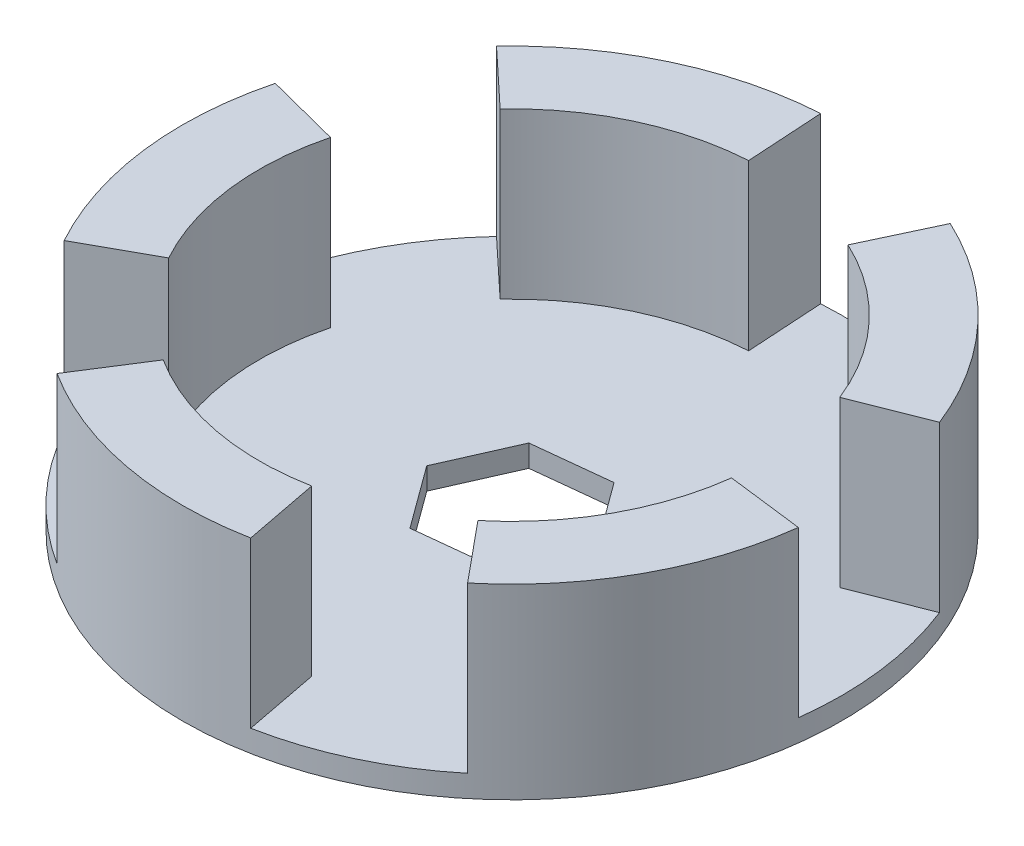
SolidWorks part; units mm, degrees
ref_plane "Front Plane" through (0, 0, 0) normal (0, 0, 1) x (1, 0, 0)
ref_plane "Top Plane" through (0, 0, 0) normal (0, 1, 0) x (1, 0, 0)
ref_plane "Right Plane" through (0, 0, 0) normal (1, 0, 0) x (0, 0, -1)
sketch "Sketch3" plane through (0, 0, 0) normal (0, 1, 0) x (1, 0, 0)
  circle A0 centre (0, 0) radius 30
  dimension "D2" = 60
extrude "Boss-Extrude3" add sketch "Sketch3" along normal blind 2
sketch "Sketch4" plane through (0, 2, 0) normal (0, 1, 0) x (1, 0, 0)
  line L0 (0, 0) -> (-16.7954, 15.7135) construction
  line L1 (0, 0) -> (9.7544, 20.8291) construction
  line L2 (0, 0) -> (21.3954, 8.4401) construction
  line L3 (0, 0) -> (22.8239, -2.8404) construction
  line L4 (0, 0) -> (14.6386, -17.7401) construction
  line L5 (0, 0) -> (4.3516, -22.5846) construction
  line L6 (0, 0) -> (-12.3483, -19.4041) construction
  line L7 (0, 0) -> (-20.1345, -11.1176) construction
  line L8 (0, 0) -> (-22.2702, 5.7477) construction
  line L9 (0, 0) -> (-1.4155, 22.9564) construction
  line L10 (-16.7954, 15.7135) -> (-1.4155, 22.9564) construction
  line L11 (-1.4155, 22.9564) -> (9.7544, 20.8291) construction
  line L12 (9.7544, 20.8291) -> (21.3954, 8.4401) construction
  line L13 (21.3954, 8.4401) -> (22.8239, -2.8404) construction
  line L14 (22.8239, -2.8404) -> (14.6386, -17.7401) construction
  line L15 (14.6386, -17.7401) -> (4.3516, -22.5846) construction
  line L16 (4.3516, -22.5846) -> (-12.3483, -19.4041) construction
  line L17 (-12.3483, -19.4041) -> (-20.1345, -11.1176) construction
  line L18 (-20.1345, -11.1176) -> (-22.2702, 5.7477) construction
  line L19 (-22.2702, 5.7477) -> (-16.7954, 15.7135) construction
  line L20 (14.6386, -17.7401) -> (19.0938, -23.1393)
  line L21 (22.8239, -2.8404) -> (29.7703, -3.7049)
  line L22 (21.3954, 8.4401) -> (27.9071, 11.0089)
  line L23 (9.7544, 20.8291) -> (12.7231, 27.1684)
  line L24 (-1.4155, 22.9564) -> (-1.8463, 29.9431)
  line L25 (-16.7954, 15.7135) -> (-21.907, 20.4959)
  line L26 (-22.2702, 5.7477) -> (-29.0482, 7.497)
  line L27 (-20.1345, -11.1176) -> (-26.2624, -14.5012)
  line L28 (-12.3483, -19.4041) -> (-16.1064, -25.3097)
  line L29 (4.3516, -22.5846) -> (5.676, -29.4582)
  circle A0 centre (0, 0) radius 23 construction
  arc A1 (-16.7954, 15.7135) -> (-1.4155, 22.9564) centre (0, 0) cw
  arc A2 (9.7544, 20.8291) -> (21.3954, 8.4401) centre (0, 0) cw
  arc A3 (22.8239, -2.8404) -> (14.6386, -17.7401) centre (0, 0) cw
  arc A4 (-12.3483, -19.4041) -> (4.3516, -22.5846) centre (0, 0) ccw
  arc A5 (-20.1345, -11.1176) -> (-22.2702, 5.7477) centre (0, 0) cw
  arc A6 (-1.8463, 29.9431) -> (-21.907, 20.4959) centre (0, 0) ccw
  arc A7 (-29.0482, 7.497) -> (-26.2624, -14.5012) centre (0, 0) ccw
  arc A8 (5.676, -29.4582) -> (-16.1064, -25.3097) centre (0, 0) cw
  arc A9 (12.7231, 27.1684) -> (27.9071, 11.0089) centre (0, 0) cw
  arc A10 (29.7703, -3.7049) -> (19.0938, -23.1393) centre (0, 0) cw
  circle A11 centre (0, 0) radius 30 construction
  dimension "D1" = 46
  dimension "D2" = 17
extrude "Boss-Extrude4" add sketch "Sketch4" along normal blind 15
sketch "Sketch5" plane through (0, 0, 0) normal (0, -1, 0) x (1, 0, 0)
  line L7 (7.0028, -0.7579) -> (4.1578, 5.6856)
  line L8 (4.1578, 5.6856) -> (-2.845, 6.4435)
  line L9 (-2.845, 6.4435) -> (-7.0028, 0.7579)
  line L10 (-7.0028, 0.7579) -> (-4.1578, -5.6856)
  line L11 (-4.1578, -5.6856) -> (2.845, -6.4435)
  line L12 (2.845, -6.4435) -> (7.0028, -0.7579)
  circle A7 centre (0, 0) radius 6.1 construction
  dimension "D1" = 12.2
extrude "Cut-Extrude1" cut sketch "Sketch5" against normal blind 10
